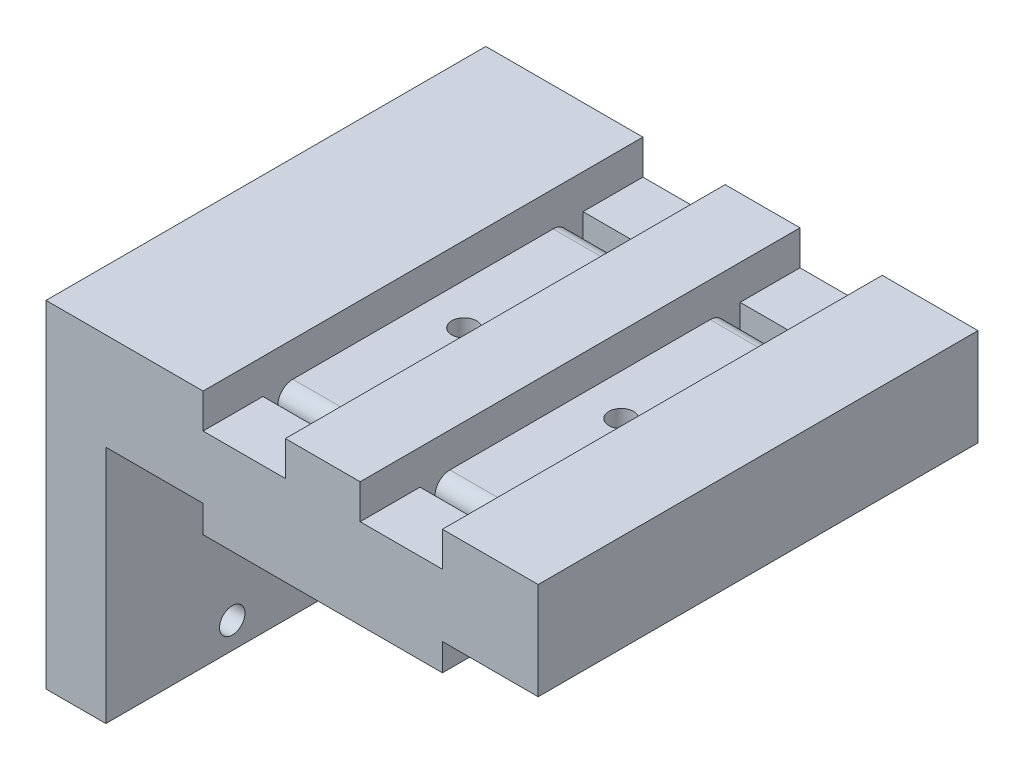
SolidWorks part; units mm, degrees
ref_plane "Front Plane" through (0, 0, 0) normal (0, 0, 1) x (1, 0, 0)
ref_plane "Top Plane" through (0, 0, 0) normal (0, 1, 0) x (1, 0, 0)
ref_plane "Right Plane" through (0, 0, 0) normal (1, 0, 0) x (0, 0, -1)
sketch "Sketch1" plane through (0, 0, 0) normal (0, 1, 0) x (1, 0, 0)
  line L1 (-28.9, 29.4) -> (28.9, 29.4)
  line L2 (-28.9, 29.4) -> (-28.9, -29.4)
  line L3 (-28.9, -29.4) -> (28.9, -29.4)
  line L4 (28.9, 29.4) -> (28.9, -29.4)
  line L5 (-28.9, 29.4) -> (28.9, -29.4) construction
  line L6 (-28.9, -29.4) -> (28.9, 29.4) construction
  point P0 (0, 0)
  dimension "D1" = 58.8
  dimension "D2" = 57.8
extrude "Boss-Extrude1" add sketch "Sketch1" along normal blind 7
sketch "Sketch5" plane through (0, 0, 0) normal (0, -1, 0) x (1, 0, 0)
  line L0 (-28.9, 29.4) -> (28.9, 29.4) construction
  line L1 (-28.9, -29.4) -> (28.9, -29.4)
  line L2 (-28.9, -29.4) -> (-28.9, 29.4)
  line L3 (-28.9, 29.4) -> (28.9, 29.4)
  line L4 (28.9, -29.4) -> (28.9, 29.4)
  point P7 (26.3737, 29.4)
extrude "Boss-Extrude2" add sketch "Sketch5" along normal blind 6
ref_plane "Plane2" through (0, -3.63, 0) normal (0, -1, 0) x (-1, 0, 0)
sketch "Sketch6" plane through (-28.9, 0, 0) normal (-1, 0, 0) x (0, 0, 1)
  line L0 (29.4, 7) -> (29.4, -6) construction
  line L1 (-29.4, 7) -> (29.4, 7)
  line L2 (-29.4, 7) -> (-29.4, -38)
  line L3 (-29.4, -38) -> (29.4, -38)
  line L4 (29.4, 7) -> (29.4, -38)
  line L5 (29.4, -6) -> (-29.4, -6) construction
  dimension "D1" = 32
extrude "Boss-Extrude3" add sketch "Sketch6" along normal blind 8
sketch "Sketch7" plane through (-36.9, 0, 0) normal (-1, 0, 0) x (0, 0, 1)
  line L0 (29.4, -38) -> (29.4, 7) construction
  line L1 (-29.4, -38) -> (29.4, -38)
  line L2 (-29.4, -38) -> (-29.4, -6)
  line L3 (-29.4, -6) -> (29.4, -6)
  line L4 (29.4, -38) -> (29.4, -6)
  line L5 (-29.4, -38) -> (29.4, -6)
  line L7 (12.5, -34.5) -> (-12.5, -34.5)
  line L8 (12.5, -34.5) -> (12.5, -9.5)
  line L9 (12.5, -9.5) -> (-12.5, -9.5)
  line L10 (-12.5, -34.5) -> (-12.5, -9.5)
  line L11 (12.5, -34.5) -> (-12.5, -9.5) construction
  line L12 (12.5, -9.5) -> (-12.5, -34.5) construction
  point P7 (0, -22)
  dimension "D1" = 25
hole_wizard "CBORE for M3 SHCS2" positions "Sketch8" profile "Sketch9" counterbore size "M3" standard "ANSI Metric" end condition through all
sketch "Sketch8" plane through (-36.9, 0, 0) normal (-1, 0, 0) x (0, 0, 1)
  point P0 (-12.5, -9.5)
  point P3 (12.5, -9.5)
  point P6 (12.5, -34.5)
  point P9 (-12.5, -34.5)
sketch "Sketch9" plane through (-36.9, -9.5, -12.5) normal (0, 1, 0) x (0, 0, 1)
  line L0 (0, 0) -> (0, 65.8)
  line L1 (0, 65.8) -> (1.7, 65.8)
  line L3 (1.7, 65.8) -> (1.7, 3)
  line L4 (1.7, 3) -> (3.25, 3)
  line L5 (3.25, 3) -> (3.25, 0)
  line L7 (3.25, 0) -> (0, 0)
  line L11 (0, -6.35) -> (0, 107.95) construction
  dimension "Thru Hole Dia." = 3.4
  dimension "Thru Hole Depth" = 65.8
  dimension "C'Bore Dia." = 6.5
  dimension "C'Bore Depth" = 3
ref_plane "Plane3" through (0, -9.63, 0) normal (0, -1, 0) x (-1, 0, 0)
ref_plane "Plane4" through (0, 2.37, 0) normal (0, -1, 0) x (-1, 0, 0)
ref_plane "Plane5" through (16.1, 0, 0) normal (1, 0, 0) x (0, 0, -1)
ref_plane "Plane6" through (-15.9, 0, 0) normal (1, 0, 0) x (0, 0, -1)
sketch "Sketch10" plane through (0, -6, 0) normal (0, -1, 0) x (1, 0, 0)
  line L0 (28.9, 29.4) -> (-28.9, 29.4) construction
  line L1 (16.1, -29.4) -> (-15.9, -29.4)
  line L2 (16.1, -29.4) -> (16.1, 29.4)
  line L3 (16.1, 29.4) -> (-15.9, 29.4)
  line L4 (-15.9, -29.4) -> (-15.9, 29.4)
  line L7 (-28.9, -29.4) -> (28.9, -29.4) construction
  line L8 (16.1, -17.6) -> (16.1, 17.6) construction
  line L9 (-15.9, -17.6) -> (-15.9, 17.6) construction
  point P7 (0, 0)
  point P9 (12.5752, -29.4)
extrude "Boss-Extrude4" add sketch "Sketch10" along normal up to surface (3.63 mm away) up to plane "Plane3"
sketch "Sketch11" plane through (0, 7, 0) normal (0, 1, 0) x (1, 0, 0)
  line L0 (-36.9, -29.4) -> (28.9, -29.4) construction
  line L1 (-15.9, -29.4) -> (16.1, -29.4)
  line L2 (-15.9, -29.4) -> (-15.9, -21.4)
  line L3 (-15.9, -21.4) -> (16.1, -21.4)
  line L4 (16.1, -29.4) -> (16.1, -21.4)
  line L10 (16.1, -17.6) -> (16.1, 17.6) construction
  line L13 (-15.9, -17.6) -> (-15.9, 17.6) construction
  dimension "D1" = 8
extrude "Cut-Extrude1" cut sketch "Sketch11" against normal up to surface (4.63 mm away)
sketch "Sketch12" plane through (0, 2.37, 0) normal (0, 1, 0) x (1, 0, 0)
  line L0 (0.1, -29.4) -> (0.1, -19.4) construction
  line L1 (-15.9, -21.4) -> (16.1, -21.4)
  line L2 (-15.9, -21.4) -> (-15.9, -19.4)
  line L3 (-15.9, -19.4) -> (16.1, -19.4)
  line L4 (16.1, -21.4) -> (16.1, -19.4)
  line L5 (-15.9, -29.4) -> (16.1, -29.4) construction
  line L6 (16.1, -21.4) -> (-15.9, -21.4) construction
  point P10 (0.7783, -13.4)
  point P11 (0, 0)
  point P12 (16.1, -17.4)
  dimension "D2" = 2
extrude "Cut-Extrude2" cut sketch "Sketch12" against normal through all and the other way through all
mirror "Mirror1" about plane through (0, 0, 0) normal (0, 0, 1) of "Cut-Extrude1", "Cut-Extrude2"
sketch "Sketch17" plane through (0, 2.37, 0) normal (0, 1, 0) x (1, 0, 0)
  line L1 (16.1, 29.4) -> (-15.9, 29.4)
  line L2 (16.1, 29.4) -> (16.1, -29.4)
  line L3 (16.1, -29.4) -> (-15.9, -29.4)
  line L4 (-15.9, 29.4) -> (-15.9, -29.4)
extrude "Cut-Extrude3" cut sketch "Sketch17" along normal blind 20
sketch "Sketch18" plane through (0, 2.37, 0) normal (0, 1, 0) x (1, 0, 0)
  line L0 (-15.9, 29.4) -> (16.1, 29.4) construction
  line L1 (5.1, 29.4) -> (-4.9, 29.4)
  line L2 (5.1, 29.4) -> (5.1, -29.4)
  line L3 (5.1, -29.4) -> (-4.9, -29.4)
  line L4 (-4.9, 29.4) -> (-4.9, -29.4)
  line L5 (-15.9, -29.4) -> (16.1, -29.4) construction
  line L6 (16.1, -29.4) -> (16.1, 29.4) construction
  line L7 (-15.9, 29.4) -> (-15.9, -29.4) construction
  dimension "D1" = 11
  dimension "D2" = 11
extrude "Boss-Extrude5" add sketch "Sketch18" along normal up to surface and the other way up to surface up to face at (22.5, 7, 0) other way up to face at (0.1, -9.63, 0)
fillet "Fillet1" radius 2 8 edges at (-10.4, -9.63, 21.4) (10.6, -9.63, 21.4) (10.6, -9.63, -21.4) (-10.4, -9.63, -21.4) (10.6, 2.37, 19.4) (-10.4, 2.37, 19.4) (-10.4, 2.37, -19.4) (10.6, 2.37, -19.4)
sketch "Sketch20" plane through (0, 2.37, 0) normal (0, 1, 0) x (1, 0, 0)
  line L0 (-4.9, 0) -> (-15.9, 0) construction
  line L1 (-4.9, 17.4) -> (-4.9, -17.4) construction
  line L2 (-15.9, 17.4) -> (-15.9, -17.4) construction
  line L3 (16.1, 0) -> (5.1, 0) construction
  line L4 (16.1, -17.4) -> (16.1, 17.4) construction
  line L5 (5.1, -17.4) -> (5.1, 17.4) construction
hole_wizard "M4x0.7 Tapped Hole1" positions "Sketch21" profile "Sketch22" tap size "M4x0.7" standard "ANSI Metric" end condition up to next
sketch "Sketch21" plane through (0, 2.37, 0) normal (0, 1, 0) x (1, 0, 0)
  line L0 (16.1, 0) -> (5.1, 0) construction
  line L1 (-4.9, 0) -> (-15.9, 0) construction
  point P0 (-10.4, 0)
  point P2 (10.6, 0)
  point P7 (0, 0)
  point P10 (0, 0)
sketch "Sketch22" plane through (-10.4, 2.37, 0) normal (1, 0, 0) x (0, 0, 1)
  line L0 (0, 0) -> (0, 12)
  line L1 (0, 12) -> (1.65, 12)
  line L2 (1.65, 12) -> (1.65, 0)
  line L5 (1.65, 0) -> (0, 0)
  line L11 (0, -6.35) -> (0, 107.95) construction
  dimension "Thru Tap Drill Dia." = 3.3
  dimension "Thru Tap Drill Depth" = 12
cosmetic thread "Hole Thread1" parameters "D2"=4
cosmetic thread "Hole Thread2" parameters "D2"=4
